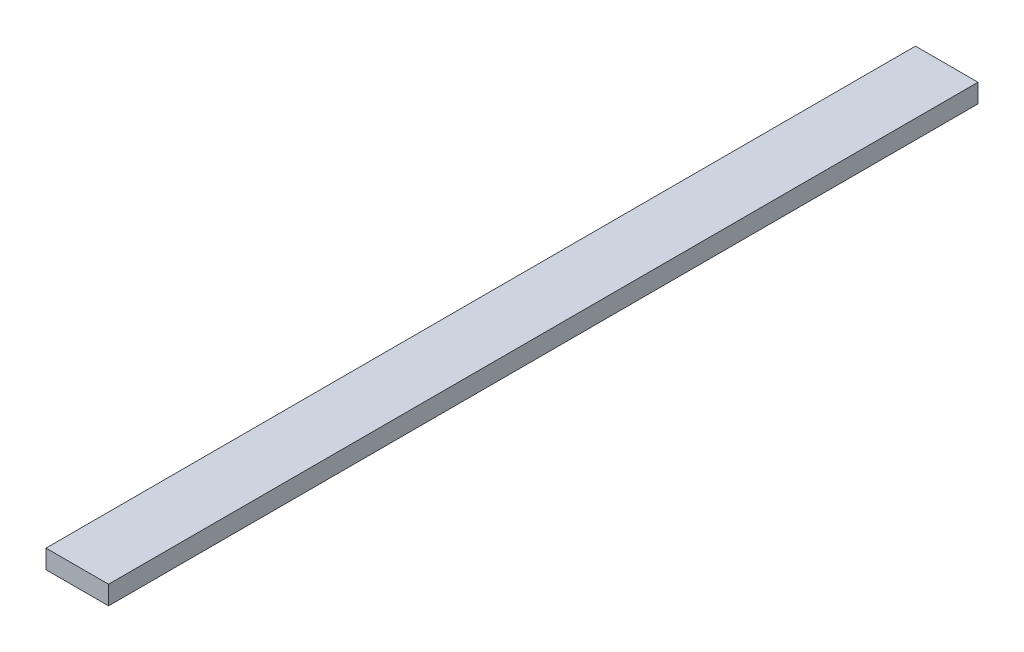
SolidWorks part; units mm, degrees
material "Copper"
ref_plane "Front Plane" through (0, 0, 0) normal (0, 0, 1) x (1, 0, 0)
ref_plane "Top Plane" through (0, 0, 0) normal (0, 1, 0) x (1, 0, 0)
ref_plane "Right Plane" through (0, 0, 0) normal (1, 0, 0) x (0, 0, -1)
ref_plane "Plane4" through (0, -16.3, 0) normal (0, -1, 0) x (1, 0, 0)
sketch "Sketch1" plane through (0, -16.3, 0) normal (0, -1, 0) x (1, 0, 0)
  line L0 (-28.3678, -81.78) -> (-18.3678, -81.78)
  line L1 (-18.3678, -81.78) -> (-18.3678, 57.22)
  line L2 (-18.3678, 57.22) -> (-28.3678, 57.22)
  line L3 (-28.3678, 57.22) -> (-28.3678, -81.78)
  dimension "D1" = 139
  dimension "D2" = 10
extrude "Boss-Extrude1" add sketch "Sketch1" against normal blind 3
